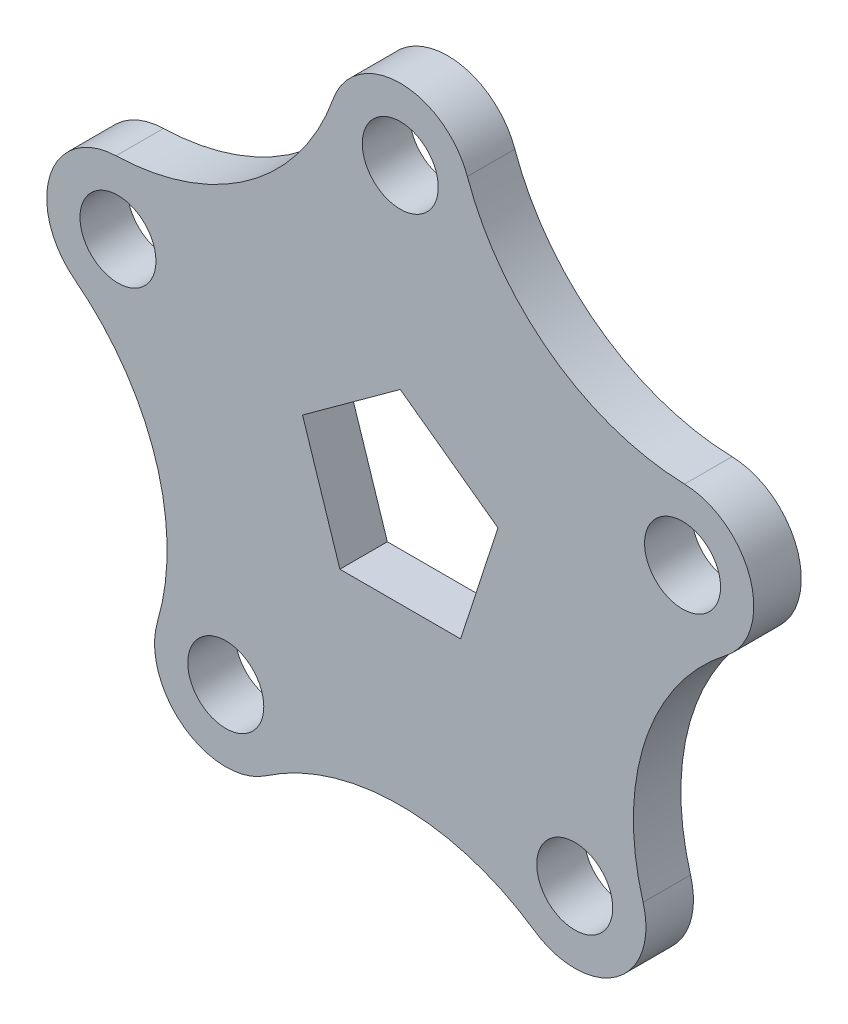
SolidWorks part; units mm, degrees
ref_plane "Front Plane" through (0, 0, 0) normal (0, 0, 1) x (1, 0, 0)
ref_plane "Top Plane" through (0, 0, 0) normal (0, 1, 0) x (1, 0, 0)
ref_plane "Right Plane" through (0, 0, 0) normal (1, 0, 0) x (0, 0, -1)
sketch "Sketch1" plane through (0, 0, 0) normal (0, 0, 1) x (1, 0, 0)
  line L0 (0, 21.6312) -> (0, 62.5) construction
  line L1 (0, 21.6312) -> (-20.5725, 6.6844)
  line L2 (-20.5725, 6.6844) -> (-12.7145, -17.5)
  line L3 (-12.7145, -17.5) -> (12.7145, -17.5)
  line L4 (12.7145, -17.5) -> (20.5725, 6.6844)
  line L5 (20.5725, 6.6844) -> (0, 21.6312)
  line L6 (-20.5725, 6.6844) -> (-59.441, 19.3136)
  line L7 (-12.7145, -17.5) -> (-36.7366, -50.5636)
  line L8 (12.7145, -17.5) -> (36.7366, -50.5636)
  line L9 (20.5725, 6.6844) -> (59.441, 19.3136)
  circle A0 centre (0, 0) radius 17.5 construction
  circle A1 centre (0, 0) radius 62.5 construction
  circle A2 centre (0, 62.5) radius 8
  arc A3 (14.1321, 67.5282) -> (-14.1321, 67.5282) centre (0, 62.5) ccw
  circle A4 centre (-59.441, 19.3136) radius 8
  arc A5 (-68.5902, 7.4269) -> (-59.856, 34.3078) centre (-59.441, 19.3136) cw
  arc A6 (-59.856, 34.3078) -> (-14.1321, 67.5282) centre (-61.2393, 84.2887) ccw
  arc A7 (-68.5902, 7.4269) -> (-51.1252, -46.3248) centre (-99.0873, -32.1954) cw
  circle A8 centre (0, 62.5) radius 8
  arc A9 (14.1321, 67.5282) -> (59.856, 34.3078) centre (61.2393, 84.2887) ccw
  arc A10 (14.1321, 67.5282) -> (-14.1321, 67.5282) centre (0, 62.5) ccw
  arc A11 (-47.7261, -40.3543) -> (-23.631, -57.8604) centre (-36.7366, -50.5636) ccw
  circle A12 centre (-36.7366, -50.5636) radius 8
  arc A13 (-28.2589, -62.9381) -> (28.2589, -62.9381) centre (0, -104.1865) cw
  arc A14 (59.856, 34.3078) -> (14.1321, 67.5282) centre (61.2393, 84.2887) cw
  arc A15 (68.5902, 7.4269) -> (51.1252, -46.3248) centre (99.0873, -32.1954) ccw
  arc A16 (68.5902, 7.4269) -> (59.856, 34.3078) centre (59.441, 19.3136) ccw
  circle A17 centre (59.441, 19.3136) radius 8
  arc A18 (-68.5902, 7.4269) -> (-51.1252, -46.3248) centre (-99.0873, -32.1954) cw
  arc A19 (23.631, -57.8604) -> (47.7261, -40.3543) centre (36.7366, -50.5636) ccw
  circle A20 centre (36.7366, -50.5636) radius 8
  point P21 (0, 0)
  point P22 (0, 0)
  dimension "D1" = 35
  dimension "D2" = 16
  dimension "D3" = 30
  dimension "D4" = 50
extrude "Boss-Extrude1" add sketch "Sketch1" along normal blind 10
